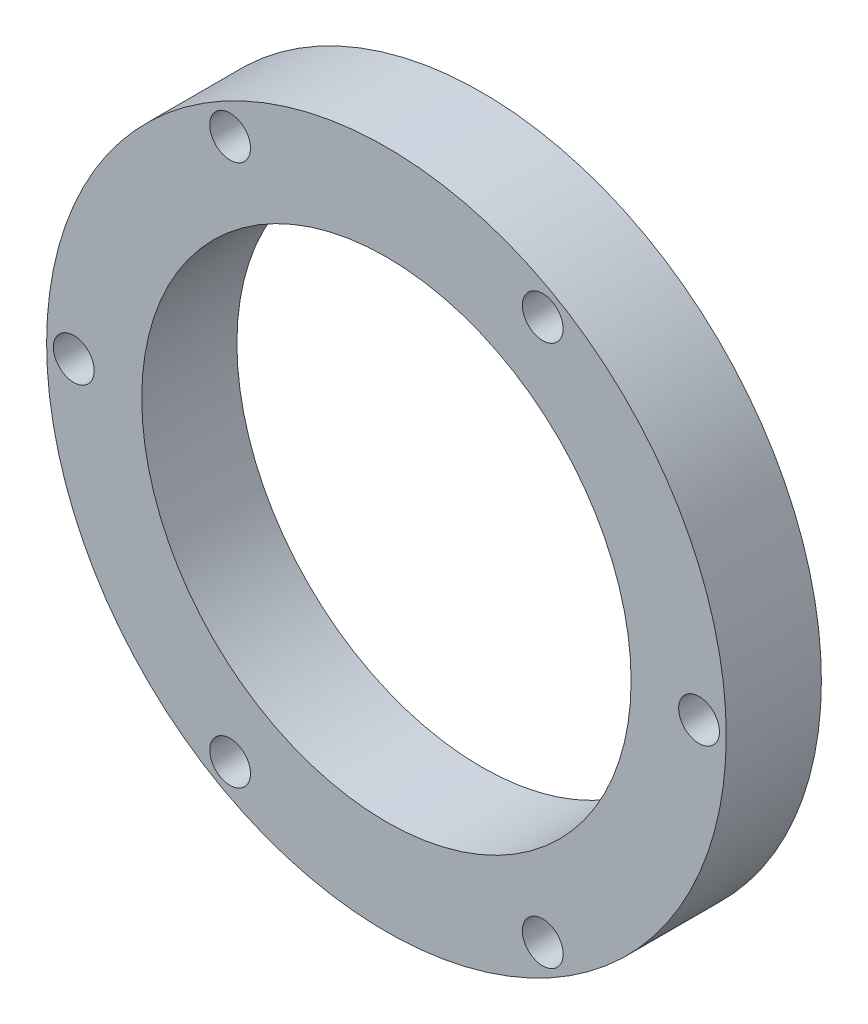
SolidWorks part; units mm, degrees
material "Acrylic (Medium-high impact)"
ref_plane "Front Plane" through (0, 0, 0) normal (0, 0, 1) x (1, 0, 0)
ref_plane "Top Plane" through (0, 0, 0) normal (0, 1, 0) x (1, 0, 0)
ref_plane "Right Plane" through (0, 0, 0) normal (1, 0, 0) x (0, 0, -1)
sketch "Sketch1" plane through (0, 0, 0) normal (0, 0, 1) x (1, 0, 0)
  line L0 (0, 34.8882) -> (0, -35.3531) construction
  line L1 (0, -35.3531) -> (0, 0) construction
  line L2 (0, 0) -> (-48.3544, 0) construction
  line L3 (-48.3544, 0) -> (47.9766, 0) construction
  line L4 (-26.5908, 46.0566) -> (27.6893, -47.9592) construction
  line L5 (27.6893, -47.9592) -> (0, 0) construction
  line L6 (0, 0) -> (21.8015, 37.7613) construction
  line L7 (0, 0) -> (-24.3439, -42.1648) construction
  circle A0 centre (0, 0) radius 25
  circle A2 centre (0, 0) radius 18
  circle A7 centre (0, 0) radius 23 construction
  circle A8 centre (-11.5, 19.9186) radius 1.5
  circle A9 centre (-23, 0) radius 1.5
  circle A10 centre (-11.5, -19.9186) radius 1.5
  circle A12 centre (11.5, -19.9186) radius 1.5
  circle A13 centre (23, 0) radius 1.5
  circle A14 centre (11.5, 19.9186) radius 1.5
  dimension "D2" = 60
  dimension "D4" = 3
  dimension "D5" = 3
  dimension "D3" = 60
extrude "Boss-Extrude1" add sketch "Sketch1" along normal blind 7
